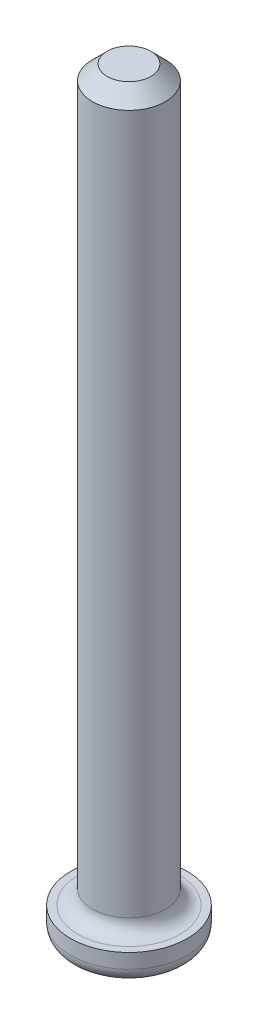
SolidWorks part; units mm, degrees
ref_plane "Front Plane" through (0, 0, 0) normal (0, 0, 1) x (1, 0, 0)
ref_plane "Top Plane" through (0, 0, 0) normal (0, 1, 0) x (1, 0, 0)
ref_plane "Right Plane" through (0, 0, 0) normal (1, 0, 0) x (0, 0, -1)
sketch "Sketch1" plane through (0, 0, 0) normal (0, 1, 0) x (1, 0, 0)
  circle A0 centre (0, 0) radius 4
  dimension "D1" = 8
extrude "Boss-Extrude1" add sketch "Sketch1" along normal blind 2
sketch "Sketch2" plane through (0, 2, 0) normal (0, 1, 0) x (1, 0, 0)
  circle A0 centre (0, 0) radius 2.5
  dimension "D1" = 5
extrude "Boss-Extrude2" add sketch "Sketch2" along normal blind 50
fillet "Fillet1" radius 1 1 edges at (0, 2, 2.5)
chamfer "Chamfer1" distance 1 angle 45 1 edges at (0, 52, 2.5)
fillet "Fillet2" radius 1 1 edges at (0, 0, 4)
